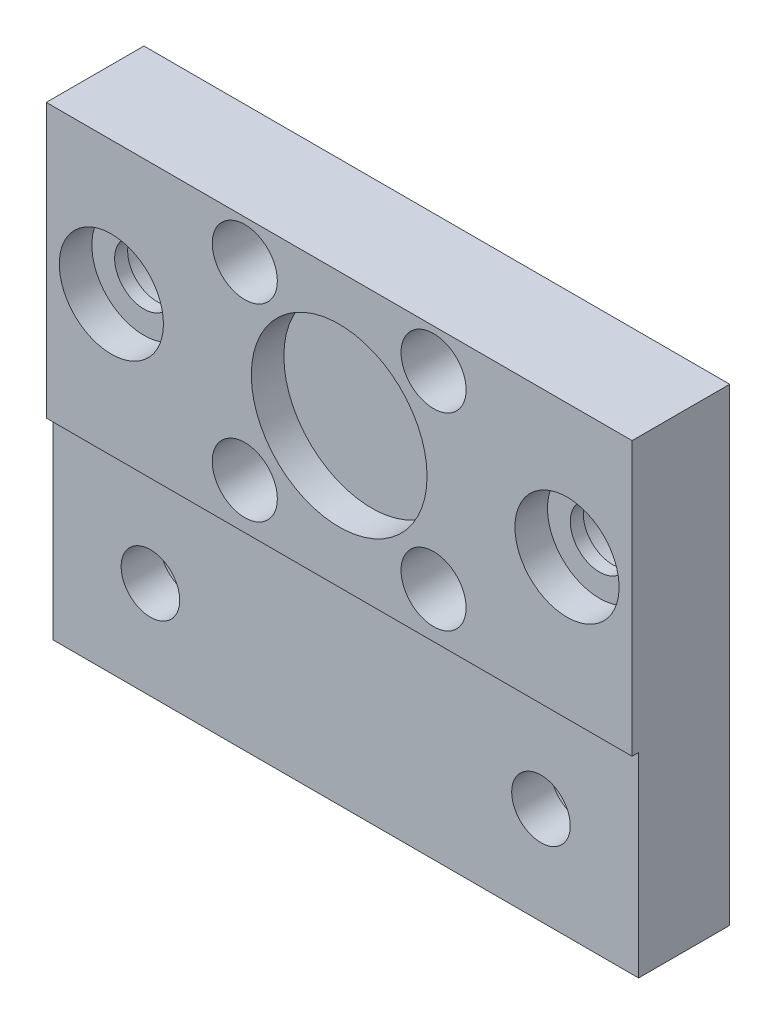
SolidWorks part; units mm, degrees
ref_plane "Front Plane" through (0, 0, 0) normal (0, 0, 1) x (1, 0, 0)
ref_plane "Top Plane" through (0, 0, 0) normal (0, 1, 0) x (1, 0, 0)
ref_plane "Right Plane" through (0, 0, 0) normal (1, 0, 0) x (0, 0, -1)
sketch "Sketch1" plane through (0, 0, 0) normal (0, 0, 1) x (1, 0, 0)
  line L1 (-45, -36) -> (45, -36)
  line L2 (-45, -36) -> (-45, 36)
  line L3 (-45, 36) -> (45, 36)
  line L4 (45, -36) -> (45, 36)
  line L5 (-45, -36) -> (45, 36) construction
  line L6 (-45, 36) -> (45, -36) construction
  point P0 (0, 0)
  dimension "D1" = 90
  dimension "D2" = 72
extrude "Boss-Extrude1" add sketch "Sketch1" along normal blind 15
sketch "Sketch2" plane through (0, 0, 15) normal (0, 0, 1) x (1, 0, 0)
  line L0 (45, -36) -> (45, 36) construction
  line L1 (-45, -36) -> (45, -36)
  line L2 (-45, -36) -> (-45, -6)
  line L3 (-45, -6) -> (45, -6)
  line L4 (45, -36) -> (45, -6)
  dimension "D1" = 30
extrude "Cut-Extrude1" cut sketch "Sketch2" against normal blind 1
sketch "Sketch3" plane through (0, 0, 15) normal (0, 0, 1) x (1, 0, 0)
  line L0 (45, 36) -> (-45, 36) construction
  line L1 (0, 0) -> (0, 36) construction
  line L2 (-14.5, 30) -> (0, 15.5) construction
  circle A0 centre (-14.5, 30) radius 5
  circle A2 centre (14.5, 30) radius 5
  circle A3 centre (14.5, 1) radius 5
  circle A4 centre (-14.5, 1) radius 5
  point P2 (-14.5, 35)
  point P3 (11.6244, 24.9424)
  point P10 (0, 0)
  point P18 (0, 15.5)
  dimension "D1" = 10
  dimension "D2" = 1
  dimension "D3" = 14.5
  dimension "D4" = 45
  dimension "D5" = 4
extrude "Cut-Extrude2" cut sketch "Sketch3" against normal through all
sketch "Sketch4" plane through (0, 0, 15) normal (0, 0, 1) x (1, 0, 0)
  line L0 (14.5, 30) -> (0, 15.5) construction
  line L1 (0, 15.5) -> (-14.5, 30) construction
  line L2 (0, 15.5) -> (0, 30.6749) construction
  circle A0 centre (0, 15.5) radius 13.5
  circle A1 centre (-35, 15.5) radius 8
  circle A2 centre (35, 15.5) radius 8
  dimension "D1" = 27
  dimension "D3" = 16
  dimension "D2" = 35
extrude "Cut-Extrude3" cut sketch "Sketch4" against normal blind 5
hole_wizard "CBORE for M8 SHCS1" positions "Sketch6" profile "Sketch8" counterbore size "M8" standard "ANSI Metric"
sketch "Sketch6" plane through (0, 0, 0) normal (0, 0, -1) x (-1, 0, 0)
  line L0 (45, -36) -> (30, -21) construction
  line L2 (45, -6) -> (45, -36) construction
  line L3 (0, -36) -> (0, 36) construction
  line L4 (45, -36) -> (-45, -36) construction
  line L5 (-45, 36) -> (45, 36) construction
  circle A0 centre (-35, 15.5) radius 8 construction
  circle A1 centre (35, 15.5) radius 8 construction
  circle A2 centre (-35, 15.5) radius 8 construction
  circle A3 centre (35, 15.5) radius 8 construction
  point P0 (30, -21)
  point P9 (-30, -21)
  point P39 (-35, 15.5)
  point P42 (35, 15.5)
  dimension "D1" = 15
  dimension "D2" = 45
sketch "Sketch8" plane through (-30, -21, 0) normal (1, 0, 0) x (0, 1, 0)
  line L0 (0, 0) -> (0, 17.7039)
  line L1 (0, 17.7039) -> (4.5, 15)
  line L2 (4.5, 15) -> (4.5, 8)
  line L3 (4.5, 8) -> (7.5, 8)
  line L4 (7.5, 8) -> (7.5, 0)
  line L5 (7.5, 0) -> (0, 0)
  line L10 (0, 17.7039) -> (-4.5, 15) construction
  line L11 (0, -6.35) -> (0, 107.95) construction
  dimension "Hole Dia." = 9
  dimension "Hole Depth" = 15
  dimension "C'Bore Dia." = 15
  dimension "C'Bore Depth" = 8
  dimension "Drill Angle" = 118
